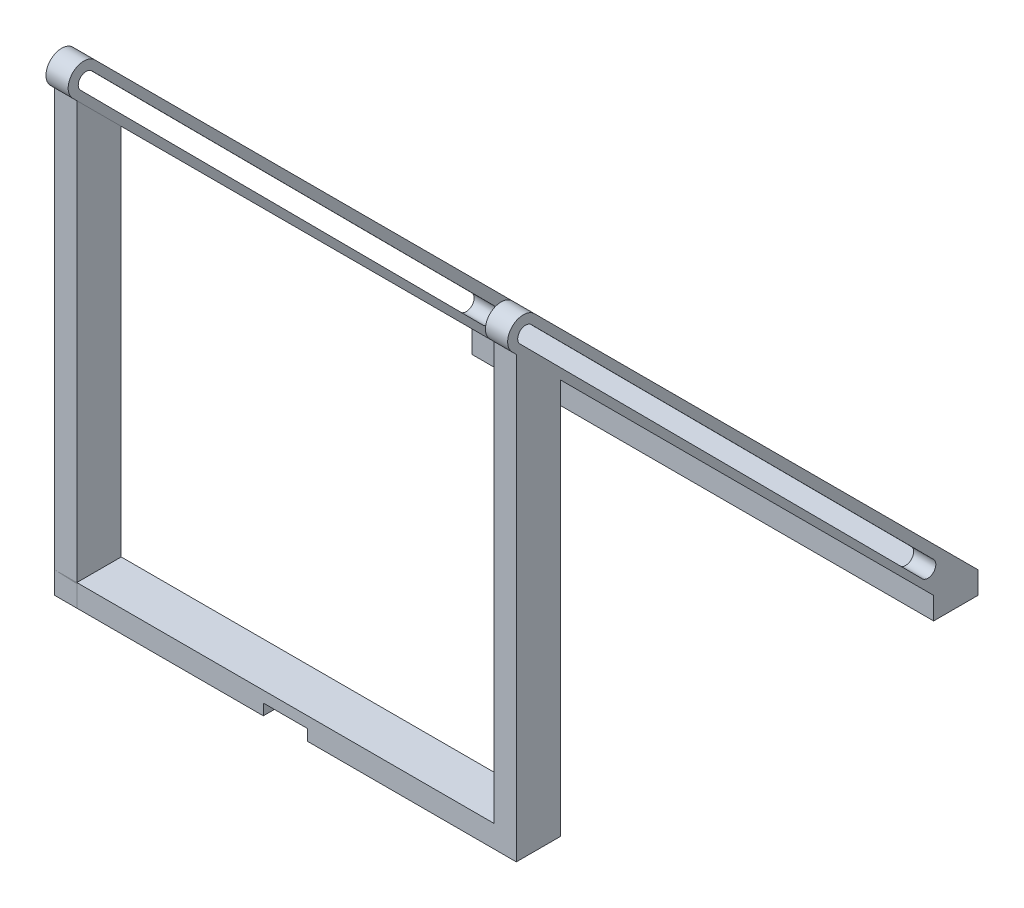
SolidWorks part; units mm, degrees
ref_plane "Front Plane" through (0, 0, 0) normal (0, 0, 1) x (1, 0, 0)
ref_plane "Top Plane" through (0, 0, 0) normal (0, 1, 0) x (1, 0, 0)
ref_plane "Right Plane" through (0, 0, 0) normal (1, 0, 0) x (0, 0, -1)
sketch "Sketch1" plane through (0, 0, 0) normal (0, 1, 0) x (1, 0, 0)
  line L0 (0, -462.534) -> (0, 462.534) construction
  line L1 (-462.534, -462.534) -> (462.534, -462.534)
  line L2 (-462.534, -462.534) -> (-462.534, 462.534)
  line L3 (-462.534, 462.534) -> (462.534, 462.534)
  line L4 (462.534, -462.534) -> (462.534, 462.534)
  line L5 (-462.534, -462.534) -> (462.534, 462.534) construction
  line L6 (-462.534, 462.534) -> (462.534, -462.534) construction
  line L8 (-44.45, -589.534) -> (44.45, -589.534)
  line L9 (-44.45, -589.534) -> (-44.45, -335.534)
  line L10 (-44.45, -335.534) -> (44.45, -335.534)
  line L11 (44.45, -589.534) -> (44.45, -335.534)
  line L12 (-44.45, -589.534) -> (44.45, -335.534) construction
  line L13 (-44.45, -335.534) -> (44.45, -589.534) construction
  point P0 (0, 0)
  dimension "D1" = 925.068
  dimension "D2" = 925.068
  dimension "D3" = 88.9
  dimension "D4" = 254
sketch "Sketch2" plane through (0, 0, 0) normal (0, 1, 0) x (1, 0, 0)
  line L0 (462.534, -462.534) -> (462.534, 462.534) construction
  line L1 (-462.534, 462.534) -> (462.534, 462.534)
  line L2 (-462.534, 462.534) -> (-462.534, 373.634)
  line L3 (-462.534, 373.634) -> (462.534, 373.634)
  line L4 (462.534, 462.534) -> (462.534, 373.634)
  line L6 (-462.534, -462.534) -> (462.534, -462.534)
  line L7 (-462.534, -462.534) -> (-462.534, -373.634)
  line L8 (-462.534, -373.634) -> (462.534, -373.634)
  line L9 (462.534, -462.534) -> (462.534, -373.634)
  dimension "D1" = 88.9
  dimension "D2" = 88.9
extrude "Boss-Extrude1" add sketch "Sketch2" along normal blind 44.45
sketch "Sketch3" plane through (-462.534, 0, 0) normal (-1, 0, 0) x (0, 0, 1)
  line L0 (-462.534, 44.45) -> (435.4916, 942.4756)
  line L1 (-462.534, 44.45) -> (-373.634, 44.45) construction
  dimension "D1" = 1270
  dimension "D2" = 45
sketch "Sketch4" plane through (0, 44.45, 0) normal (0, 1, 0) x (1, 0, 0)
  line L0 (-462.534, 373.634) -> (462.534, 373.634) construction
  line L1 (-462.534, 462.534) -> (-418.084, 462.534)
  line L2 (-462.534, 462.534) -> (-462.534, 373.634)
  line L3 (-462.534, 373.634) -> (-418.084, 373.634)
  line L4 (-418.084, 462.534) -> (-418.084, 373.634)
  dimension "D1" = 44.45
sweep "Sweep1" add profiles "Sketch4" path "Sketch3"
fillet "Fillet1" radius 31.4309 4 edges at (-462.534, 942.4756, 479.9416) (-440.309, 942.4756, 524.3916) (-418.084, 942.4756, 479.9416) (-440.309, 942.4756, 435.4916)
sketch "Sketch5" plane through (-462.534, 0, 0) normal (-1, 0, 0) x (0, 0, 1)
  line L0 (470.7357, 933.2697) -> (-457.4104, 0) construction
  line L1 (462.534, 0) -> (-462.534, 0) construction
  line L2 (-362.1261, 95.8103) -> (443.8692, 906.2549) construction
  line L3 (-373.3823, 107.0046) -> (432.613, 917.4493)
  line L4 (-350.87, 84.6159) -> (455.1254, 895.0605)
  arc A0 (470.7357, 888.8197) -> (426.2857, 933.2697) centre (448.5107, 911.0447) ccw construction
  arc A1 (-373.3823, 107.0046) -> (-350.87, 84.6159) centre (-362.1261, 95.8103) ccw
  arc A2 (455.1254, 895.0605) -> (432.613, 917.4493) centre (443.8692, 906.2549) ccw
  point P9 (40.8715, 501.0326)
  point P14 (0, 0)
  dimension "D4" = 38.1
  dimension "D1" = 1316.2247
  dimension "D2" = 31.75
  dimension "D3" = 1143
extrude "Cut-Extrude1" cut sketch "Sketch5" against normal blind 44.45
sketch "Sketch6" plane through (0, 44.45, 0) normal (0, 1, 0) x (1, 0, 0)
  line L0 (462.534, -373.634) -> (-462.534, -373.634) construction
  line L1 (-462.534, -462.534) -> (-418.084, -462.534)
  line L2 (-462.534, -462.534) -> (-462.534, -373.634)
  line L3 (-462.534, -373.634) -> (-418.084, -373.634)
  line L4 (-418.084, -462.534) -> (-418.084, -373.634)
  dimension "D1" = 44.45
extrude "Boss-Extrude2" add sketch "Sketch6" along normal up to surface and the other way blind 44.45 separate body up to face at (-440.309, 466.6349, 48.5509)
mirror "Mirror4" about plane through (0, 0, 0) normal (1, 0, 0) of "Boss-Extrude2"
mirror "Mirror8" about plane through (0, 0, 0) normal (1, 0, 0) of "Fillet1", "Cut-Extrude1", "Sweep1"
extrude "Cut-Extrude2" cut sketch "Sketch1" along normal blind 22.225 contours L9 L10 L11 L8
